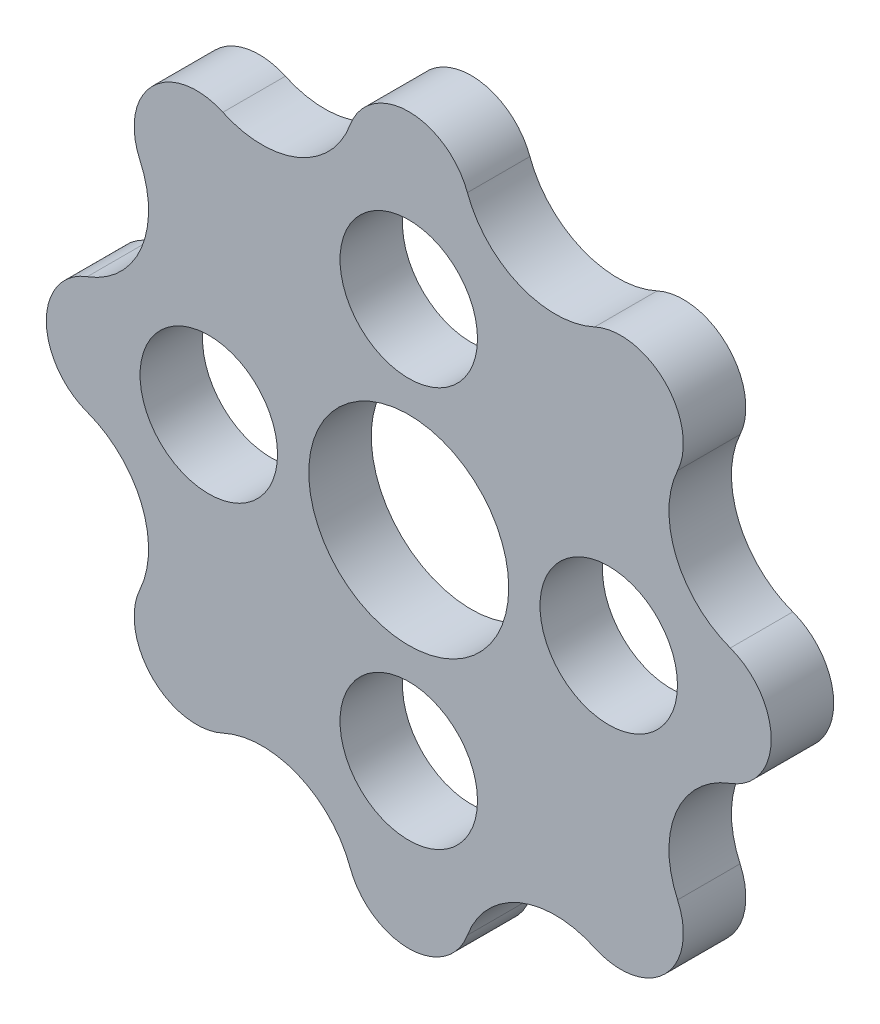
SolidWorks part; units mm, degrees
ref_plane "前视基准面" through (0, 0, 0) normal (0, 0, 1) x (1, 0, 0)
ref_plane "上视基准面" through (0, 0, 0) normal (0, 1, 0) x (1, 0, 0)
ref_plane "右视基准面" through (0, 0, 0) normal (1, 0, 0) x (0, 0, -1)
other "Configuration Table"
sketch "草图1" plane through (0, 0, 0) normal (0, 0, 1) x (1, 0, 0)
  arc A0 (9.3841, 51.4552) -> (-9.3841, 51.4552) centre (0, 48) ccw
  arc A1 (43.0199, 29.7488) -> (29.7488, 43.0199) centre (33.9411, 33.9411) ccw
  arc A2 (51.4552, -9.3841) -> (51.4552, 9.3841) centre (48, 0) ccw
  arc A3 (29.7488, -43.0199) -> (43.0199, -29.7488) centre (33.9411, -33.9411) ccw
  arc A4 (-9.3841, -51.4552) -> (9.3841, -51.4552) centre (0, -48) ccw
  arc A5 (-43.0199, -29.7488) -> (-29.7488, -43.0199) centre (-33.9411, -33.9411) ccw
  arc A6 (-51.4552, 9.3841) -> (-51.4552, -9.3841) centre (-48, 0) ccw
  arc A7 (-29.7488, 43.0199) -> (-43.0199, 29.7488) centre (-33.9411, 33.9411) ccw
  arc A8 (-29.7488, 43.0199) -> (-9.3841, 51.4552) centre (-23.4603, 56.6381) ccw
  arc A9 (9.3841, 51.4552) -> (29.7488, 43.0199) centre (23.4603, 56.6381) ccw
  arc A10 (43.0199, 29.7488) -> (51.4552, 9.3841) centre (56.6381, 23.4603) ccw
  arc A11 (51.4552, -9.3841) -> (43.0199, -29.7488) centre (56.6381, -23.4603) ccw
  arc A12 (29.7488, -43.0199) -> (9.3841, -51.4552) centre (23.4603, -56.6381) ccw
  arc A13 (-9.3841, -51.4552) -> (-29.7488, -43.0199) centre (-23.4603, -56.6381) ccw
  arc A14 (-43.0199, -29.7488) -> (-51.4552, -9.3841) centre (-56.6381, -23.4603) ccw
  arc A15 (-51.4552, 9.3841) -> (-43.0199, 29.7488) centre (-56.6381, 23.4603) ccw
  point P20 (0, 0)
  point P44 (0, 0)
  dimension "D1" = 20
  dimension "D4" = 30
  dimension "D2" = 48
  dimension "D3" = 8
  dimension "D5" = 8
extrude "凸台-拉伸1" add sketch "草图1" along normal blind 10
sketch "草图2" plane through (0, 0, 10) normal (0, 0, 1) x (1, 0, 0)
  circle A0 centre (0, 0) radius 16
  circle A1 centre (0, 0) radius 32 construction
  circle A2 centre (0, 32) radius 11
  circle A3 centre (32, 0) radius 11
  circle A4 centre (0, -32) radius 11
  circle A5 centre (-32, 0) radius 11
  point P15 (0, 0)
  dimension "D1" = 22
  dimension "D2" = 64
  dimension "D3" = 32
  dimension "D4" = 4
extrude "切除-拉伸1" cut sketch "草图2" against normal blind 10
